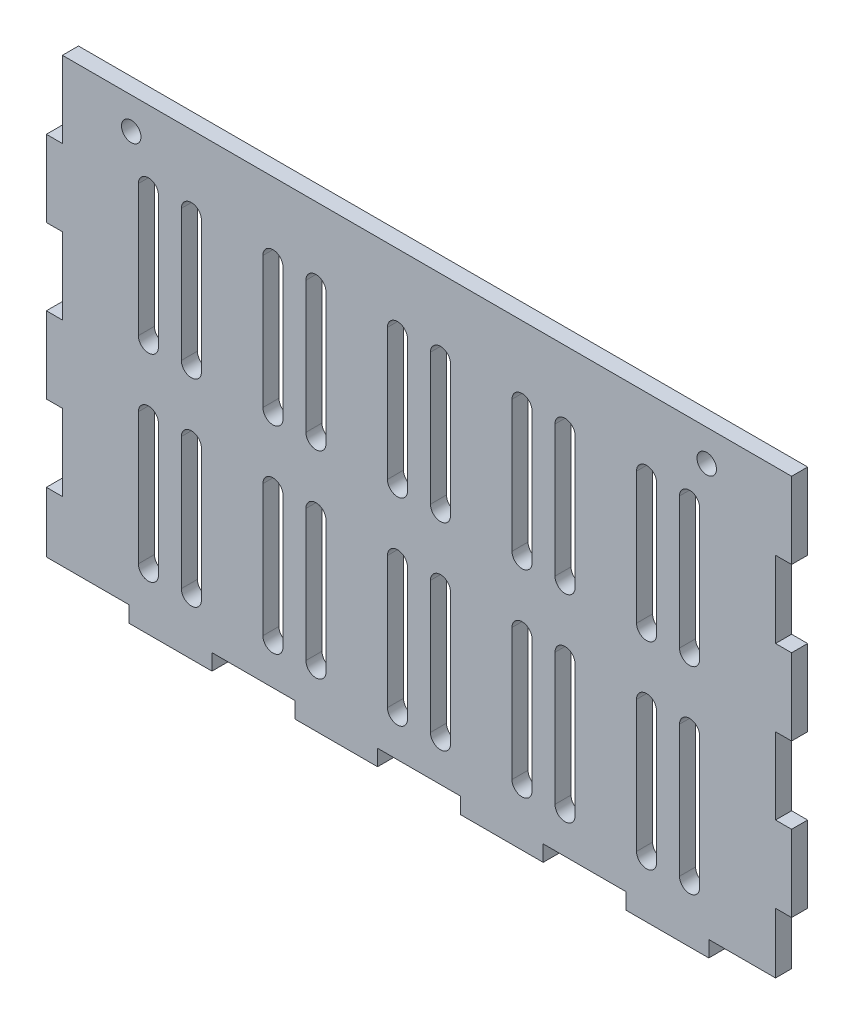
SolidWorks part; units mm, degrees
material "Acrylic (Medium-high impact)"
ref_plane "Front Plane" through (0, 0, 0) normal (0, 0, 1) x (1, 0, 0)
ref_plane "Top Plane" through (0, 0, 0) normal (0, 1, 0) x (1, 0, 0)
ref_plane "Right Plane" through (0, 0, 0) normal (1, 0, 0) x (0, 0, -1)
sketch "Sketch1" plane through (0, 0, 0) normal (0, 0, 1) x (1, 0, 0)
  line L1 (0, 0) -> (130, 0)
  line L2 (0, 0) -> (0, 80)
  line L3 (0, 80) -> (130, 80)
  line L4 (130, 0) -> (130, 80)
  dimension "D1" = 130
  dimension "D2" = 80
extrude "Boss-Extrude1" add sketch "Sketch1" along normal blind 2.8
sketch "Sketch2" plane through (0, 0, 2.8) normal (0, 0, 1) x (1, 0, 0)
  line L61 (14.4444, 2.8) -> (28.8889, 2.8) construction
  line L62 (0, 0) -> (14.4444, 0)
  line L67 (0, 0) -> (0, 2.8)
  line L72 (0, 2.8) -> (14.4444, 2.8)
  line L77 (14.4444, 0) -> (14.4444, 2.8)
  line L97 (28.8889, 0) -> (28.8889, 2.8)
  line L98 (28.8889, 0) -> (43.3333, 0)
  line L107 (43.3333, 0) -> (43.3333, 2.8)
  line L115 (28.8889, 2.8) -> (43.3333, 2.8)
  line L117 (43.3333, 2.8) -> (57.7778, 2.8) construction
  line L123 (57.7778, 0) -> (57.7778, 2.8)
  line L128 (57.7778, 0) -> (72.2222, 0)
  line L129 (72.2222, 0) -> (72.2222, 2.8)
  line L131 (57.7778, 2.8) -> (72.2222, 2.8)
  line L132 (72.2222, 2.8) -> (86.6667, 2.8) construction
  line L133 (86.6667, 0) -> (86.6667, 2.8)
  line L134 (86.6667, 0) -> (101.1111, 0)
  line L135 (101.1111, 0) -> (101.1111, 2.8)
  line L136 (86.6667, 2.8) -> (101.1111, 2.8)
  line L137 (101.1111, 2.8) -> (115.5556, 2.8) construction
  line L138 (115.5556, 0) -> (115.5556, 2.8)
  line L139 (115.5556, 0) -> (130, 0)
  line L142 (130, 0) -> (130, 80) construction
  line L143 (0, 80) -> (0, 0) construction
  line L144 (0, 13.3333) -> (2.8, 13.3333)
  line L145 (0, 13.3333) -> (0, 26.6667)
  line L146 (130, 2.8) -> (144.4444, 2.8) construction
  line L147 (0, 26.6667) -> (2.8, 26.6667)
  line L148 (2.8, 13.3333) -> (2.8, 26.6667)
  line L149 (2.8, 13.3333) -> (2.8, 0) construction
  line L150 (0, 40) -> (0, 53.3333)
  line L151 (0, 40) -> (2.8, 40)
  line L152 (2.8, 40) -> (2.8, 53.3333)
  line L153 (0, 53.3333) -> (2.8, 53.3333)
  line L154 (2.8, 40) -> (2.8, 26.6667) construction
  line L155 (0, 66.6667) -> (0, 80)
  line L156 (0, 66.6667) -> (2.8, 66.6667)
  line L157 (2.8, 66.6667) -> (2.8, 80)
  line L158 (0, 80) -> (2.8, 80)
  line L159 (2.8, 66.6667) -> (2.8, 53.3333) construction
  line L160 (130, 80) -> (0, 80) construction
  line L161 (127.2, 80) -> (127.2, 66.6667) construction
  line L162 (127.2, 40) -> (127.2, 26.6667)
  line L163 (127.2, 66.6667) -> (130, 66.6667)
  line L164 (127.2, 66.6667) -> (127.2, 53.3333)
  line L165 (127.2, 53.3333) -> (130, 53.3333)
  line L166 (130, 66.6667) -> (130, 53.3333)
  line L167 (127.2, 40) -> (130, 40)
  line L168 (130, 40) -> (130, 26.6667)
  line L169 (127.2, 26.6667) -> (130, 26.6667)
  line L170 (127.2, 53.3333) -> (127.2, 40) construction
  line L172 (127.2, 13.3333) -> (130, 13.3333)
  line L173 (130, 13.3333) -> (130, 0)
  line L175 (127.2, 26.6667) -> (127.2, 13.3333) construction
  line L183 (115.5556, 2.8) -> (130, 2.8) [skipped]
  line L184 (130, 0) -> (130, 2.8) [skipped]
  line L185 (127.2, 13.3333) -> (127.2, 2.8)
  line L186 (127.2, 2.8) -> (115.5556, 2.8)
  line L187 (127.2, 0) -> (130, 0) [skipped]
  line L188 (127.2, 13.3333) -> (127.2, 0) [skipped]
  dimension "D2" = 2.8
  dimension "D4" = 2.8
  dimension "D6" = 2.8
  dimension "D1" = 5
  dimension "D3" = 3
  dimension "D5" = 3
extrude "Cut-Extrude1" cut sketch "Sketch2" against normal through all
sketch "Sketch3" plane through (0, 0, 2.8) normal (0, 0, 1) x (1, 0, 0)
  line L0 (0, 66.6667) -> (0, 53.3333) construction
  line L1 (130, 80) -> (2.8, 80) construction
  line L2 (0, 66.6667) -> (130, 66.6667) construction
  line L3 (65, 66.6667) -> (65, 50066.6667) construction
  circle A0 centre (14.8, 74.5) radius 1.7
  circle A1 centre (115.2, 74.5) radius 1.7
  point P10 (65, 66.6667)
  dimension "D1" = 3.4
  dimension "D2" = 14.8
  dimension "D3" = 5.5
extrude "Cut-Extrude2" cut sketch "Sketch3" against normal up to next
sketch "Sketch4" plane through (0, 0, 2.8) normal (0, 0, 1) x (1, 0, 0)
  line L0 (17.8, 9.8) -> (17.8, 32.775) construction
  line L1 (16.05, 9.8) -> (16.05, 32.775)
  line L2 (19.55, 9.8) -> (19.55, 32.775)
  line L3 (17.8, 44.275) -> (17.8, 67.25) construction
  line L4 (16.05, 44.275) -> (16.05, 67.25)
  line L5 (19.55, 44.275) -> (19.55, 67.25)
  line L6 (25.3, 9.8) -> (25.3, 32.775) construction
  line L7 (23.55, 9.8) -> (23.55, 32.775)
  line L8 (27.05, 9.8) -> (27.05, 32.775)
  line L9 (25.3, 44.275) -> (25.3, 67.25) construction
  line L10 (23.55, 44.275) -> (23.55, 67.25)
  line L11 (27.05, 44.275) -> (27.05, 67.25)
  line L13 (130, 80) -> (2.8, 80) construction
  line L14 (14.4444, 2.8) -> (0, 2.8) construction
  line L15 (41.275, 9.8) -> (41.275, 32.775)
  line L17 (37.775, 9.8) -> (37.775, 32.775)
  line L18 (48.775, 9.8) -> (48.775, 32.775)
  line L19 (45.275, 9.8) -> (45.275, 32.775)
  line L20 (48.775, 44.275) -> (48.775, 67.25)
  line L21 (45.275, 44.275) -> (45.275, 67.25)
  line L22 (41.275, 44.275) -> (41.275, 67.25)
  line L23 (37.775, 44.275) -> (37.775, 67.25)
  line L24 (39.525, 9.8) -> (39.525, 32.775) construction
  line L25 (39.525, 44.275) -> (39.525, 67.25) construction
  line L26 (47.025, 9.8) -> (47.025, 32.775) construction
  line L27 (47.025, 44.275) -> (47.025, 67.25) construction
  line L28 (63, 9.8) -> (63, 32.775)
  line L29 (59.5, 9.8) -> (59.5, 32.775)
  line L30 (70.5, 9.8) -> (70.5, 32.775)
  line L31 (67, 9.8) -> (67, 32.775)
  line L32 (70.5, 44.275) -> (70.5, 67.25)
  line L33 (67, 44.275) -> (67, 67.25)
  line L34 (63, 44.275) -> (63, 67.25)
  line L35 (59.5, 44.275) -> (59.5, 67.25)
  line L36 (61.25, 9.8) -> (61.25, 32.775) construction
  line L37 (61.25, 44.275) -> (61.25, 67.25) construction
  line L38 (68.75, 9.8) -> (68.75, 32.775) construction
  line L39 (68.75, 44.275) -> (68.75, 67.25) construction
  line L40 (84.725, 9.8) -> (84.725, 32.775)
  line L41 (81.225, 9.8) -> (81.225, 32.775)
  line L42 (92.225, 9.8) -> (92.225, 32.775)
  line L43 (88.725, 9.8) -> (88.725, 32.775)
  line L44 (92.225, 44.275) -> (92.225, 67.25)
  line L45 (88.725, 44.275) -> (88.725, 67.25)
  line L46 (84.725, 44.275) -> (84.725, 67.25)
  line L47 (81.225, 44.275) -> (81.225, 67.25)
  line L48 (82.975, 9.8) -> (82.975, 32.775) construction
  line L49 (82.975, 44.275) -> (82.975, 67.25) construction
  line L50 (90.475, 9.8) -> (90.475, 32.775) construction
  line L51 (90.475, 44.275) -> (90.475, 67.25) construction
  line L52 (106.45, 9.8) -> (106.45, 32.775)
  line L53 (102.95, 9.8) -> (102.95, 32.775)
  line L54 (113.95, 9.8) -> (113.95, 32.775)
  line L55 (110.45, 9.8) -> (110.45, 32.775)
  line L56 (113.95, 44.275) -> (113.95, 67.25)
  line L57 (110.45, 44.275) -> (110.45, 67.25)
  line L58 (106.45, 44.275) -> (106.45, 67.25)
  line L59 (102.95, 44.275) -> (102.95, 67.25)
  line L60 (104.7, 9.8) -> (104.7, 32.775) construction
  line L61 (104.7, 44.275) -> (104.7, 67.25) construction
  line L62 (112.2, 9.8) -> (112.2, 32.775) construction
  line L63 (112.2, 44.275) -> (112.2, 67.25) construction
  line L64 (17.8, 21.2875) -> (2.8, 21.2875) construction
  line L65 (2.8, 13.3333) -> (2.8, 26.6667) construction
  line L66 (112.2, 21.2875) -> (127.2, 21.2875) construction
  line L67 (127.2, 26.6667) -> (127.2, 13.3333) construction
  line L68 (17.8, 32.775) -> (25.3, 32.775) construction
  arc A0 (16.05, 9.8) -> (19.55, 9.8) centre (17.8, 9.8) ccw
  arc A1 (19.55, 32.775) -> (16.05, 32.775) centre (17.8, 32.775) ccw
  arc A2 (16.05, 44.275) -> (19.55, 44.275) centre (17.8, 44.275) ccw
  arc A3 (19.55, 67.25) -> (16.05, 67.25) centre (17.8, 67.25) ccw
  arc A4 (23.55, 9.8) -> (27.05, 9.8) centre (25.3, 9.8) ccw
  arc A5 (27.05, 32.775) -> (23.55, 32.775) centre (25.3, 32.775) ccw
  arc A6 (23.55, 44.275) -> (27.05, 44.275) centre (25.3, 44.275) ccw
  arc A7 (27.05, 67.25) -> (23.55, 67.25) centre (25.3, 67.25) ccw
  arc A8 (37.775, 9.8) -> (41.275, 9.8) centre (39.525, 9.8) ccw
  arc A9 (41.275, 32.775) -> (37.775, 32.775) centre (39.525, 32.775) ccw
  arc A10 (45.275, 9.8) -> (48.775, 9.8) centre (47.025, 9.8) ccw
  arc A11 (48.775, 32.775) -> (45.275, 32.775) centre (47.025, 32.775) ccw
  arc A12 (45.275, 44.275) -> (48.775, 44.275) centre (47.025, 44.275) ccw
  arc A13 (48.775, 67.25) -> (45.275, 67.25) centre (47.025, 67.25) ccw
  arc A14 (37.775, 44.275) -> (41.275, 44.275) centre (39.525, 44.275) ccw
  arc A15 (41.275, 67.25) -> (37.775, 67.25) centre (39.525, 67.25) ccw
  arc A16 (59.5, 9.8) -> (63, 9.8) centre (61.25, 9.8) ccw
  arc A17 (63, 32.775) -> (59.5, 32.775) centre (61.25, 32.775) ccw
  arc A18 (67, 9.8) -> (70.5, 9.8) centre (68.75, 9.8) ccw
  arc A19 (70.5, 32.775) -> (67, 32.775) centre (68.75, 32.775) ccw
  arc A20 (67, 44.275) -> (70.5, 44.275) centre (68.75, 44.275) ccw
  arc A21 (70.5, 67.25) -> (67, 67.25) centre (68.75, 67.25) ccw
  arc A22 (59.5, 44.275) -> (63, 44.275) centre (61.25, 44.275) ccw
  arc A23 (63, 67.25) -> (59.5, 67.25) centre (61.25, 67.25) ccw
  arc A24 (81.225, 9.8) -> (84.725, 9.8) centre (82.975, 9.8) ccw
  arc A25 (84.725, 32.775) -> (81.225, 32.775) centre (82.975, 32.775) ccw
  arc A26 (88.725, 9.8) -> (92.225, 9.8) centre (90.475, 9.8) ccw
  arc A27 (92.225, 32.775) -> (88.725, 32.775) centre (90.475, 32.775) ccw
  arc A28 (88.725, 44.275) -> (92.225, 44.275) centre (90.475, 44.275) ccw
  arc A29 (92.225, 67.25) -> (88.725, 67.25) centre (90.475, 67.25) ccw
  arc A30 (81.225, 44.275) -> (84.725, 44.275) centre (82.975, 44.275) ccw
  arc A31 (84.725, 67.25) -> (81.225, 67.25) centre (82.975, 67.25) ccw
  arc A32 (102.95, 9.8) -> (106.45, 9.8) centre (104.7, 9.8) ccw
  arc A33 (106.45, 32.775) -> (102.95, 32.775) centre (104.7, 32.775) ccw
  arc A34 (110.45, 9.8) -> (113.95, 9.8) centre (112.2, 9.8) ccw
  arc A35 (113.95, 32.775) -> (110.45, 32.775) centre (112.2, 32.775) ccw
  arc A36 (110.45, 44.275) -> (113.95, 44.275) centre (112.2, 44.275) ccw
  arc A37 (113.95, 67.25) -> (110.45, 67.25) centre (112.2, 67.25) ccw
  arc A38 (102.95, 44.275) -> (106.45, 44.275) centre (104.7, 44.275) ccw
  arc A39 (106.45, 67.25) -> (102.95, 67.25) centre (104.7, 67.25) ccw
  point P2 (17.8, 21.2875)
  point P7 (17.8, 55.7625)
  point P14 (25.3, 21.2875)
  point P21 (25.3, 55.7625)
  point P36 (39.525, 21.2875)
  point P41 (39.525, 55.7625)
  point P48 (47.025, 21.2875)
  point P55 (47.025, 55.7625)
  point P64 (61.25, 21.2875)
  point P69 (61.25, 55.7625)
  point P76 (68.75, 21.2875)
  point P83 (68.75, 55.7625)
  point P92 (82.975, 21.2875)
  point P97 (82.975, 55.7625)
  point P104 (90.475, 21.2875)
  point P111 (90.475, 55.7625)
  point P120 (104.7, 21.2875)
  point P125 (104.7, 55.7625)
  point P132 (112.2, 21.2875)
  point P139 (112.2, 55.7625)
  dimension "D3" = 11
  dimension "D5" = 8
  dimension "D1" = 3.5
  dimension "D2" = 4
  dimension "D4" = 7
  dimension "D7" = 15
  dimension "D6" = 5
extrude "Cut-Extrude3" cut sketch "Sketch4" against normal up to next
other "Width tolerance" face at (128.6, 53.3333, 1.4) face at (128.6, 26.6667, 1.4) face at (128.6, 13.3333, 1.4) face at (128.6, 40, 1.4) face at (128.6, 66.6667, 1.4) face at (115.5556, 1.4, 1.4) face at (86.6667, 1.4, 1.4) face at (57.7778, 1.4, 1.4) face at (28.8889, 1.4, 1.4) face at (14.4444, 1.4, 1.4) face at (43.3333, 1.4, 1.4) face at (72.2222, 1.4, 1.4) face at (101.1111, 1.4, 1.4) face at (1.4, 26.6667, 1.4) face at (1.4, 13.3333, 1.4) face at (1.4, 40, 1.4) face at (1.4, 53.3333, 1.4) face at (1.4, 66.6667, 1.4) parameters "D1"=0
equation "\"wall_thickness\"= 2.8mm"
equation "\"D1@Boss-Extrude1\"=\"wall_thickness\""
equation "\"slot_width_tolerance\"= 0.0mm"
equation "\"slot_depth\" = 2.8mm"
equation "\"D2@Sketch2\"=\"slot_depth\""
equation "\"D4@Sketch2\"=\"slot_depth\""
equation "\"D6@Sketch2\"=\"slot_depth\""
equation "\"D2@Sketch3\"=12.00mm+\"slot_depth\""
equation "\"D1@Width tolerance\" = \"slot_width_tolerance\""
